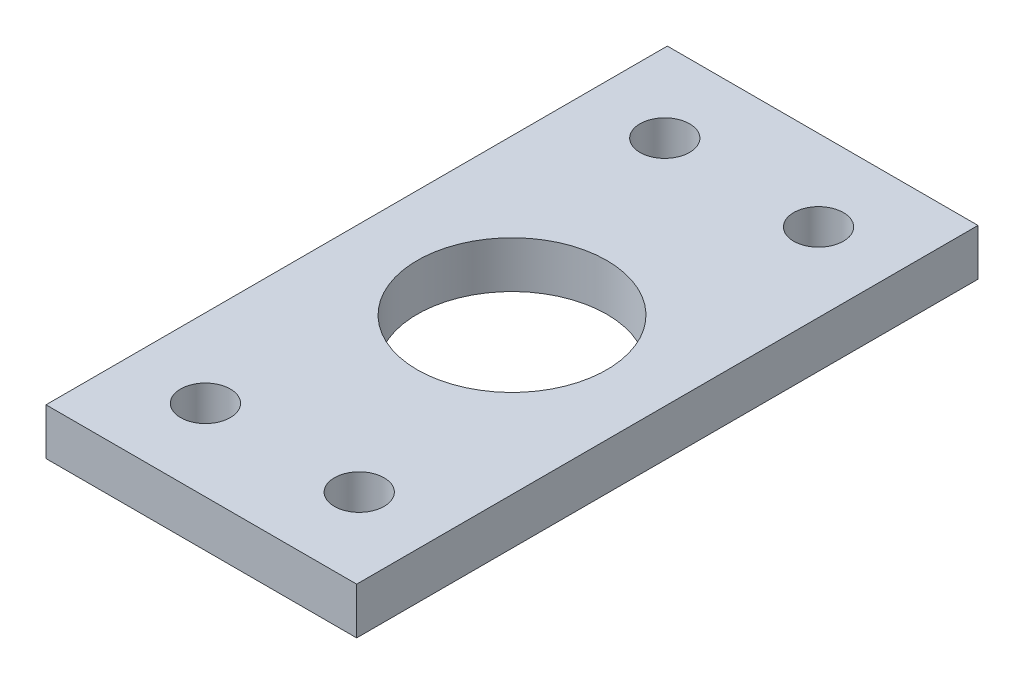
SolidWorks part; units mm, degrees
ref_plane "前视基准面" through (0, 0, 0) normal (0, 0, 1) x (1, 0, 0)
ref_plane "上视基准面" through (0, 0, 0) normal (0, 1, 0) x (1, 0, 0)
ref_plane "右视基准面" through (0, 0, 0) normal (1, 0, 0) x (0, 0, -1)
sketch "草图1" plane through (0, 0, 0) normal (0, 1, 0) x (1, 0, 0)
  line L0 (-10, 0) -> (10, 0) construction
  line L1 (-10, -20) -> (10, -20)
  line L2 (-10, -20) -> (-10, 20)
  line L3 (-10, 20) -> (10, 20)
  line L4 (10, -20) -> (10, 20)
  line L5 (-10, -20) -> (10, 20) construction
  line L6 (-10, 20) -> (10, -20) construction
  line L7 (-4.95, -14.785) -> (4.95, -14.785) construction
  line L8 (-4.95, -14.785) -> (-4.95, 14.785) construction
  line L9 (-4.95, 14.785) -> (4.95, 14.785) construction
  line L10 (4.95, -14.785) -> (4.95, 14.785) construction
  line L11 (-4.95, -14.785) -> (4.95, 14.785) construction
  line L12 (-4.95, 14.785) -> (4.95, -14.785) construction
  line L13 (0, 20) -> (0, -20) construction
  circle A0 centre (0, 0) radius 6.1
  circle A1 centre (4.95, 14.785) radius 1.6
  circle A2 centre (4.95, -14.785) radius 1.6
  circle A3 centre (-4.95, 14.785) radius 1.6
  circle A4 centre (-4.95, -14.785) radius 1.6
  point P0 (0, 0)
  dimension "D1" = 12.2
  dimension "D4" = 3.2
  dimension "D2" = 29.57
  dimension "D3" = 9.9
  dimension "D5" = 40
  dimension "D6" = 20
extrude "凸台-拉伸1" add sketch "草图1" along normal blind 3
